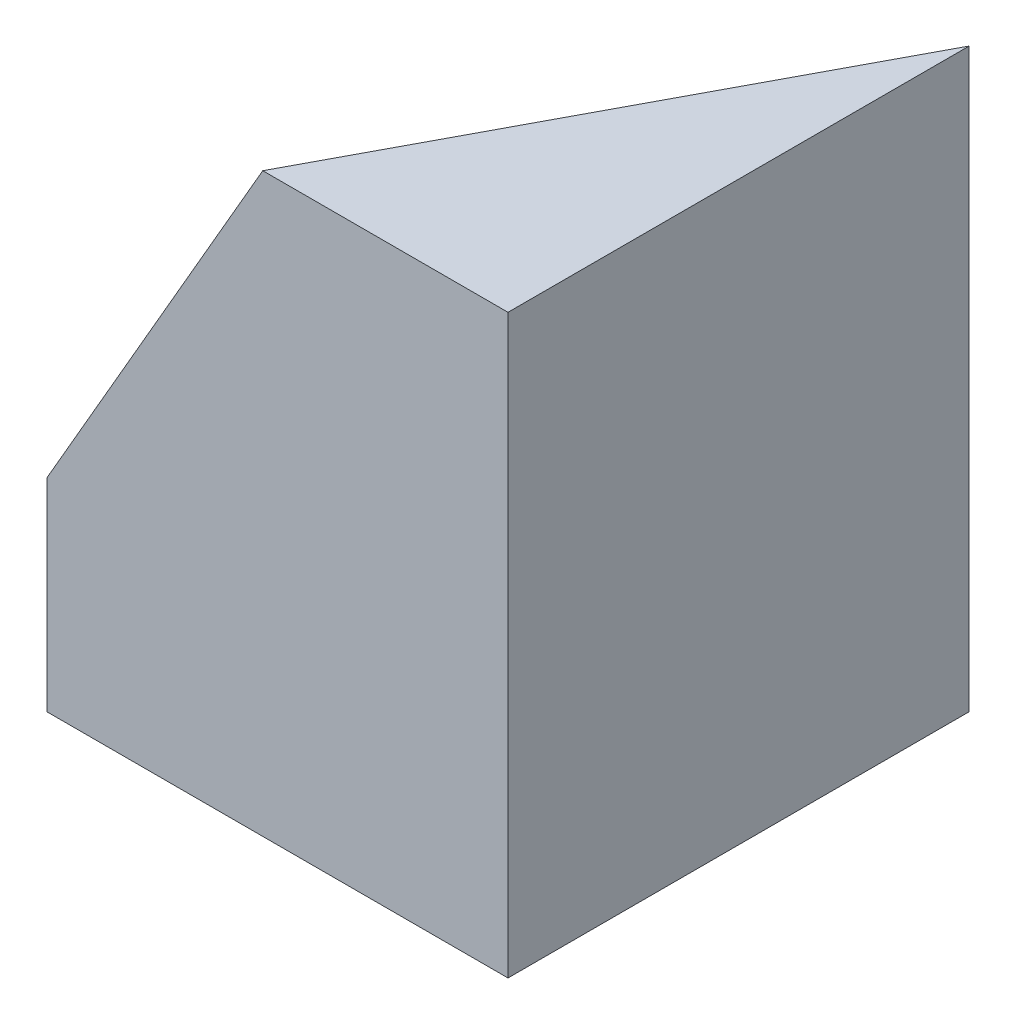
SolidWorks part; units mm, degrees
ref_plane "前视基准面" through (0, 0, 0) normal (0, 0, 1) x (1, 0, 0)
ref_plane "上视基准面" through (0, 0, 0) normal (0, 1, 0) x (1, 0, 0)
ref_plane "右视基准面" through (0, 0, 0) normal (1, 0, 0) x (0, 0, -1)
other "Configuration Table"
sketch "草图1" plane through (0, 0, 0) normal (0, 1, 0) x (1, 0, 0)
  line L1 (-24, -24) -> (24, -24)
  line L2 (-24, -24) -> (-24, 24)
  line L3 (-24, 24) -> (24, 24)
  line L4 (24, -24) -> (24, 24)
  line L5 (-24, -24) -> (24, 24) construction
  line L6 (-24, 24) -> (24, -24) construction
  point P0 (0, 0)
  dimension "D1" = 48
extrude "凸台-拉伸1" add sketch "草图1" along normal blind 60
sketch3d "3D草图1"
  line L0 (24, 60, -24) -> (-1.5221, 60, 24)
  line L1 (24, 60, -24) -> (-24, 60, -24) construction
  line L2 (24, 60, 24) -> (24, 60, -24) construction
  line L3 (-24, 60, 24) -> (24, 60, 24) construction
  line L4 (-1.5221, 60, 24) -> (-24, 21.0671, 24)
  line L5 (-24, 60, 24) -> (-24, 0, 24) construction
  line L6 (-24, 21.0671, 24) -> (-24, 0, 1.1246)
  line L7 (-24, 0, -24) -> (-24, 0, 24) construction
  line L8 (-24, 0, 1.1246) -> (-10.641, 0, -24)
  line L9 (24, 0, -24) -> (-24, 0, -24) construction
  line L10 (-10.641, 0, -24) -> (24, 60, -24)
  line L11 (-24, 0, 24) -> (24, 0, 24) construction
  dimension "D1" = 62
  dimension "D2" = 60
  dimension "D3" = 60
  dimension "D4" = 62
ref_plane "基准面1" through (-14.481, 8.3606, -7.6997) normal (0.7866, -0.4542, 0.4183) x (0.3622, -0.2091, -0.9083)
other "使用曲面切除1"
